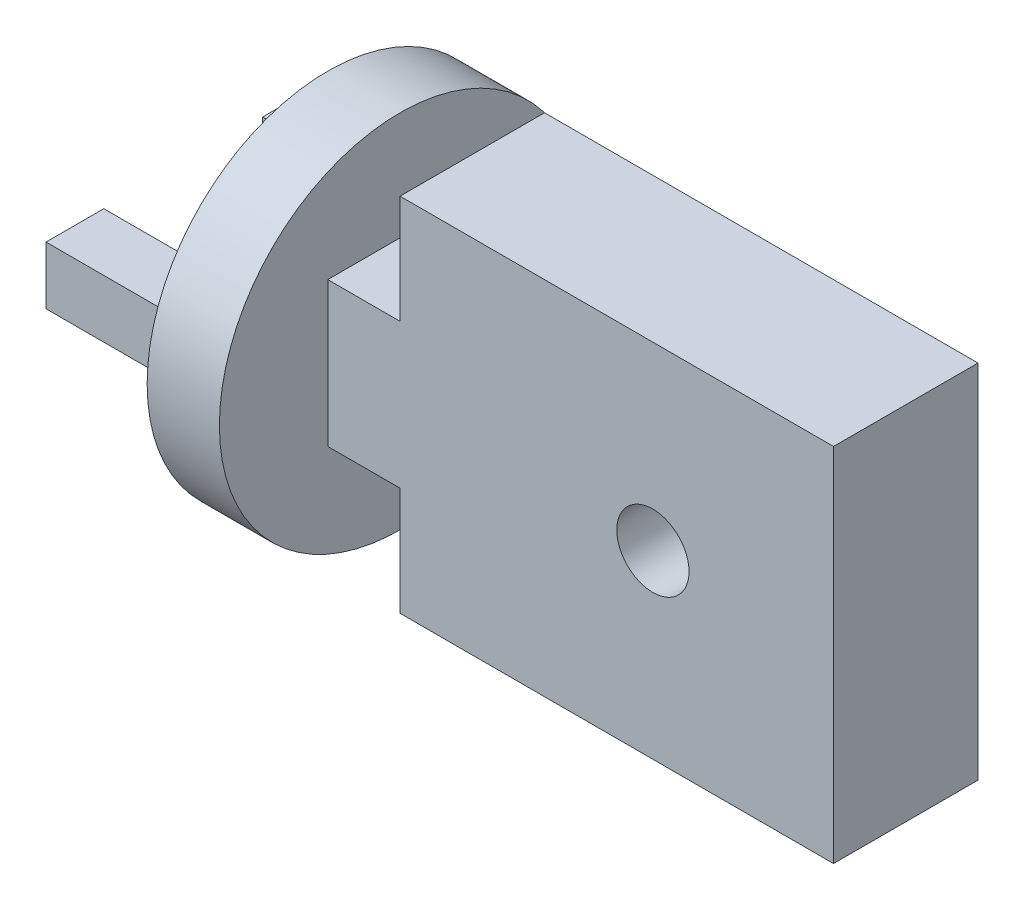
SolidWorks part; units mm, degrees
ref_plane "Front Plane" through (0, 0, 0) normal (0, 0, 1) x (1, 0, 0)
ref_plane "Top Plane" through (0, 0, 0) normal (0, 1, 0) x (1, 0, 0)
ref_plane "Right Plane" through (0, 0, 0) normal (1, 0, 0) x (0, 0, -1)
sketch "Sketch1" plane through (0, 0, 0) normal (0, 0, 1) x (1, 0, 0)
  line L1 (-76.2, 63.5) -> (76.2, 63.5)
  line L2 (-76.2, 63.5) -> (-76.2, -63.5)
  line L3 (-76.2, -63.5) -> (76.2, -63.5)
  line L4 (76.2, 63.5) -> (76.2, -63.5)
  line L5 (-76.2, 63.5) -> (76.2, -63.5) construction
  line L6 (-76.2, -63.5) -> (76.2, 63.5) construction
  point P0 (0, 0)
  dimension "D1" = 152.4
  dimension "D2" = 127
extrude "Boss-Extrude1" add sketch "Sketch1" along normal blind 127
sketch "Sketch2" plane through (-76.2, 0, 0) normal (-1, 0, 0) x (0, 0, 1)
  line L0 (127, 63.5) -> (0, 63.5) construction
  line L1 (38.1, 25.4) -> (88.9, 25.4)
  line L2 (38.1, 25.4) -> (38.1, -25.4)
  line L3 (38.1, -25.4) -> (88.9, -25.4)
  line L4 (88.9, 25.4) -> (88.9, -25.4)
  line L5 (38.1, 25.4) -> (88.9, -25.4) construction
  line L6 (38.1, -25.4) -> (88.9, 25.4) construction
  line L8 (127, 63.5) -> (127, -63.5) construction
  point P0 (63.5, 0)
  dimension "D1" = 63.5
  dimension "D2" = 63.5
  dimension "D3" = 50.8
  dimension "D4" = 50.8
extrude "Boss-Extrude2" add sketch "Sketch2" along normal blind 25.4
sketch "Sketch3" plane through (-101.6, 0, 0) normal (-1, 0, 0) x (0, 0, 1)
  line L0 (88.9, 25.4) -> (38.1, 25.4) construction
  line L1 (38.1, 25.4) -> (38.1, -25.4) construction
  circle A0 centre (63.5, 0) radius 63.5
  dimension "D3" = 127
  dimension "D1" = 25.4
  dimension "D2" = 25.4
extrude "Boss-Extrude3" add sketch "Sketch3" along normal blind 25.4
sketch "Sketch4" plane through (-127, 0, 0) normal (-1, 0, 0) x (0, 0, 1)
  line L1 (15.24, 10.16) -> (35.56, 10.16)
  line L2 (15.24, 10.16) -> (15.24, -10.16)
  line L3 (15.24, -10.16) -> (35.56, -10.16)
  line L4 (35.56, 10.16) -> (35.56, -10.16)
  line L5 (15.24, 10.16) -> (35.56, -10.16) construction
  line L6 (15.24, -10.16) -> (35.56, 10.16) construction
  line L7 (91.44, 10.16) -> (111.76, 10.16)
  line L8 (91.44, 10.16) -> (91.44, -10.16)
  line L9 (91.44, -10.16) -> (111.76, -10.16)
  line L10 (111.76, 10.16) -> (111.76, -10.16)
  line L11 (91.44, 10.16) -> (111.76, -10.16) construction
  line L12 (91.44, -10.16) -> (111.76, 10.16) construction
  circle A0 centre (63.5, 0) radius 63.5 construction
  point P0 (25.4, 0)
  point P5 (101.6, 0)
  dimension "D1" = 25.4
  dimension "D2" = 38.1
  dimension "D3" = 20.32
  dimension "D4" = 20.32
  dimension "D5" = 20.32
  dimension "D6" = 20.32
extrude "Boss-Extrude4" add sketch "Sketch4" along normal blind 50.8
sketch "Sketch5" plane through (0, 63.5, 0) normal (0, 1, 0) x (1, 0, 0)
  line L1 (76.2, -127) -> (-76.2, -127)
  line L2 (76.2, -127) -> (76.2, -88.9)
  line L3 (76.2, -88.9) -> (-76.2, -88.9)
  line L4 (-76.2, -127) -> (-76.2, -88.9)
  line L5 (76.2, 0) -> (-76.2, 0)
  line L6 (76.2, 0) -> (76.2, -38.1)
  line L7 (76.2, -38.1) -> (-76.2, -38.1)
  line L8 (-76.2, 0) -> (-76.2, -38.1)
  dimension "D1" = 38.1
  dimension "D2" = 152.4
  dimension "D3" = 38.1
  dimension "D4" = 152.4
extrude "Cut-Extrude1" cut sketch "Sketch5" against normal through all
sketch "Sketch6" plane through (0, 0, 88.9) normal (0, 0, 1) x (1, 0, 0)
  line L0 (76.2, -63.5) -> (76.2, 63.5) construction
  circle A0 centre (12.7, 0) radius 12.7
  dimension "D2" = 25.4
  dimension "D1" = 63.5
extrude "Cut-Extrude2" cut sketch "Sketch6" against normal through all
